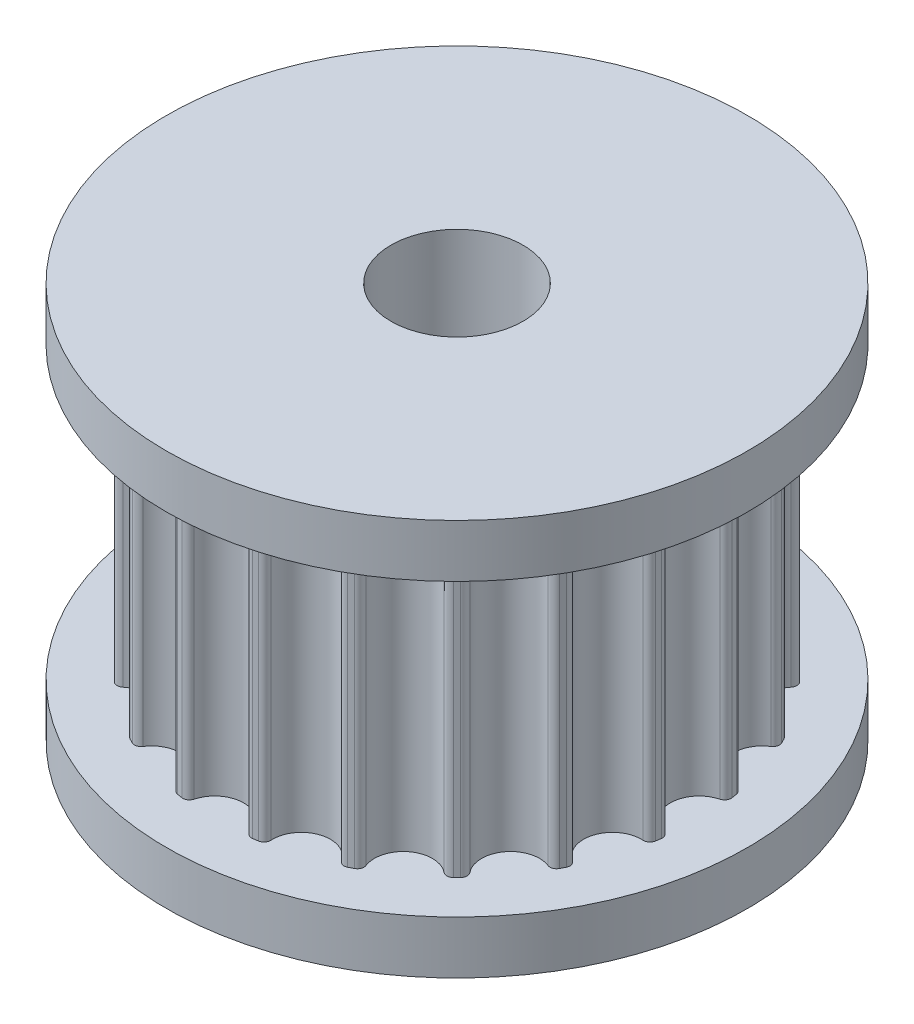
SolidWorks part; units mm, degrees
material "1060 合金"
ref_plane "前视基准面" through (0, 0, 0) normal (0, 0, 1) x (1, 0, 0)
ref_plane "上视基准面" through (0, 0, 0) normal (0, 1, 0) x (1, 0, 0)
ref_plane "右视基准面" through (0, 0, 0) normal (1, 0, 0) x (0, 0, -1)
other "Configuration Table"
sketch "草图1" plane through (0, 0, 0) normal (0, 1, 0) x (1, 0, 0)
  circle A0 centre (0, 0) radius 9.17
  dimension "D1" = 18.34
extrude "凸台-拉伸1" add sketch "草图1" against normal blind 11
sketch "草图2" plane through (0, 0, 0) normal (0, 1, 0) x (1, 0, 0)
  line L0 (0, -1000) -> (0, 49000) construction
  line L9 (-1.3385, 9.0718) -> (-1.302, 9.5481)
  line L10 (-1.302, 9.5481) -> (1.1645, 9.509)
  line L11 (1.1645, 9.509) -> (1.3385, 9.0718)
  arc A13 (-1.0603, 8.8886) -> (1.0603, 8.8886) centre (0, 9.17) ccw
  arc A14 (1.3385, 9.0718) -> (1.0603, 8.8886) centre (1.302, 8.8245) ccw
  arc A15 (-1.3385, 9.0718) -> (-1.0603, 8.8886) centre (-1.302, 8.8245) cw
extrude "切除-拉伸1" cut sketch "草图2" against normal blind 11
pattern_circular "阵列(圆周)1" count 20 over 360 about axis through (0, 0, 0) along (0, 1, 0) of "切除-拉伸1"
sketch "草图3" plane through (0, -11, 0) normal (0, -1, 0) x (1, 0, 0)
  circle A1 centre (0, 0) radius 11
sketch "草图4" plane through (0, 0, 0) normal (0, 1, 0) x (1, 0, 0)
  circle A0 centre (0, 0) radius 11
extrude "凸台-拉伸3" add sketch "草图4" along normal blind 2
extrude "凸台-拉伸4" add sketch "草图3" along normal blind 2
sketch "草图5" plane through (0, 2, 0) normal (0, 1, 0) x (1, 0, 0)
  circle A0 centre (0, 0) radius 2.5
extrude "切除-拉伸2" cut sketch "草图5" against normal blind 22
